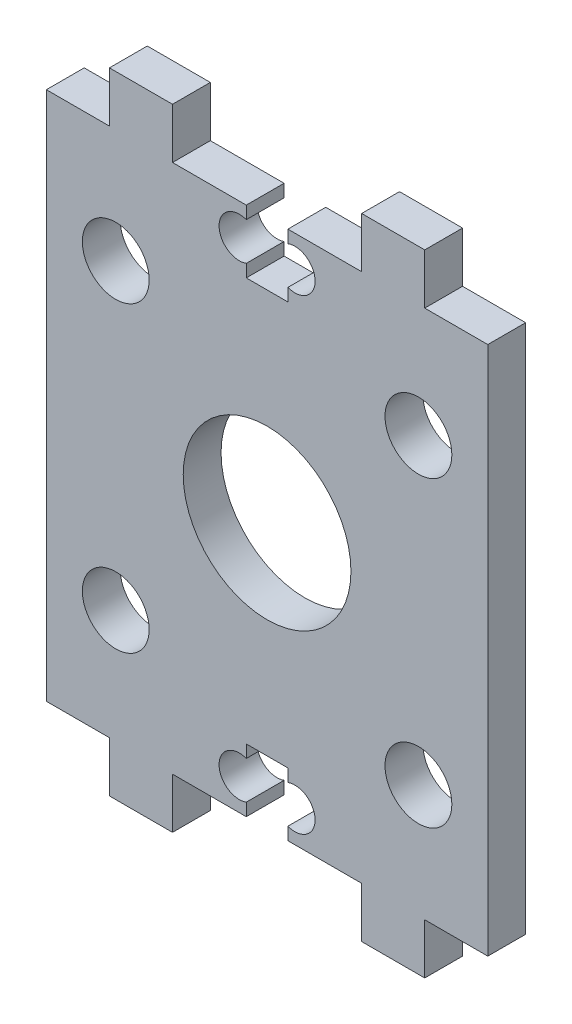
SolidWorks part; units mm, degrees
material "Thornel Mat VMA"
ref_plane "前视基准面" through (0, 0, 0) normal (0, 0, 1) x (1, 0, 0)
ref_plane "上视基准面" through (0, 0, 0) normal (0, 1, 0) x (1, 0, 0)
ref_plane "右视基准面" through (0, 0, 0) normal (1, 0, 0) x (0, 0, -1)
sketch "草图1" plane through (0, 0, 0) normal (0, 0, 1) x (1, 0, 0)
  line L0 (0, 0) -> (17.5, 0) construction
  line L1 (17.5, -21) -> (-17.5, -21) construction
  line L2 (17.5, -21) -> (17.5, 21)
  line L3 (17.5, 21) -> (-17.5, 21) construction
  line L4 (-17.5, -21) -> (-17.5, 21)
  line L5 (17.5, -21) -> (-17.5, 21) construction
  line L6 (17.5, 21) -> (-17.5, -21) construction
  line L7 (0, 0) -> (11.9996, -11.9996) construction
  line L8 (-17.5, 21) -> (-12.5, 21)
  line L9 (-12.5, 21) -> (-12.5, 25)
  line L10 (-12.5, 25) -> (-7.5, 25)
  line L11 (-7.5, 25) -> (-7.5, 21)
  line L12 (-7.5, 21) -> (-1.65, 21)
  line L13 (-1.65, 21) -> (-1.65, 20)
  line L14 (-1.65, 20) -> (-1.65, 17) construction
  line L15 (-1.65, 17) -> (-1.65, 16)
  line L16 (-1.65, 16) -> (1.65, 16)
  line L20 (1.65, 21) -> (7.5, 21)
  line L21 (7.5, 21) -> (7.5, 25)
  line L22 (7.5, 25) -> (12.5, 25)
  line L23 (12.5, 25) -> (12.5, 21)
  line L24 (12.5, 21) -> (17.5, 21)
  line L25 (1.65, 16) -> (1.65, 17)
  line L26 (1.65, 17) -> (1.65, 20) construction
  line L27 (1.65, 20) -> (1.65, 21)
  line L28 (12.5, -21) -> (17.5, -21)
  line L29 (12.5, -25) -> (12.5, -21)
  line L30 (7.5, -25) -> (12.5, -25)
  line L31 (7.5, -21) -> (7.5, -25)
  line L32 (1.65, -20) -> (1.65, -21)
  line L33 (1.65, -21) -> (7.5, -21)
  line L34 (-1.65, -20) -> (-1.65, -17) construction
  line L35 (-1.65, -17) -> (-1.65, -16)
  line L36 (-1.65, -16) -> (1.65, -16)
  line L37 (1.65, -17) -> (1.65, -20) construction
  line L38 (1.65, -16) -> (1.65, -17)
  line L39 (-1.65, -21) -> (-1.65, -20)
  line L40 (-7.5, -21) -> (-1.65, -21)
  line L41 (-7.5, -25) -> (-7.5, -21)
  line L42 (-12.5, -25) -> (-7.5, -25)
  line L43 (-17.5, -21) -> (-12.5, -21)
  line L44 (-12.5, -21) -> (-12.5, -25)
  circle A0 centre (0, 0) radius 16.97 construction
  circle A1 centre (0, 0) radius 6.65
  circle A2 centre (11.9996, -11.9996) radius 2.65
  circle A3 centre (-11.9996, -11.9996) radius 2.65
  circle A4 centre (-11.9996, 11.9996) radius 2.65
  circle A5 centre (11.9996, 11.9996) radius 2.65
  arc A6 (-1.65, 20) -> (-1.65, 17) centre (-2.2068, 18.5) ccw
  arc A7 (1.65, 17) -> (1.65, 20) centre (2.2068, 18.5) ccw
  arc A8 (-1.65, -20) -> (-1.65, -17) centre (-2.2068, -18.5) cw
  arc A9 (1.65, -17) -> (1.65, -20) centre (2.2068, -18.5) cw
  point P0 (0, 0)
  point P21 (0, 0)
  point P29 (0, 21)
  point P31 (0, 16)
  point P50 (0, -16)
  dimension "D3" = 33.94
  dimension "D4" = 13.3
  dimension "D6" = 5.3
  dimension "D18" = 3.2
  dimension "D1" = 35
  dimension "D2" = 42
  dimension "D5" = 45
  dimension "D8" = 5
  dimension "D9" = 5
  dimension "D10" = 4
  dimension "D11" = 3.3
  dimension "D12" = 5
  dimension "D13" = 4
  dimension "D14" = 5
  dimension "D15" = 5
  dimension "D16" = 3
  dimension "D17" = 1
  dimension "D7" = 4
extrude "凸台-拉伸1" add sketch "草图1" along normal blind 3
